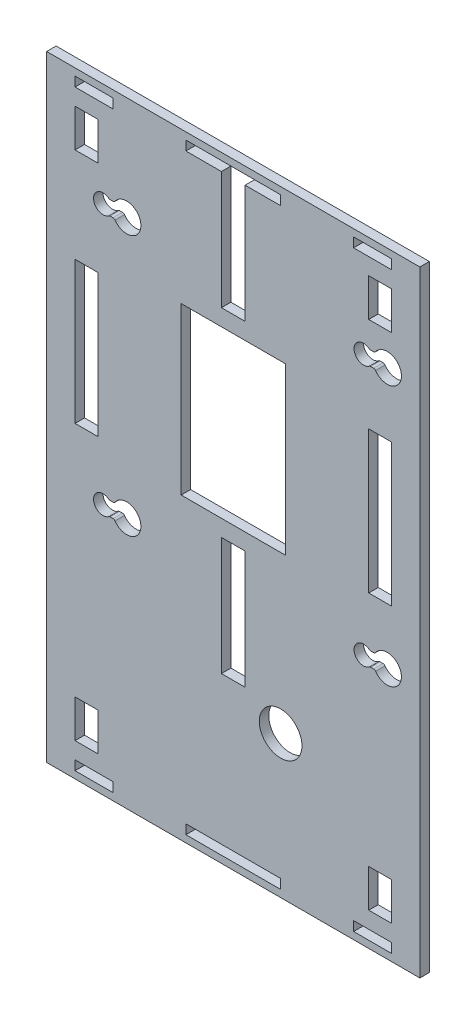
SolidWorks part; units mm, degrees
ref_plane "Front Plane" through (0, 0, 0) normal (0, 0, 1) x (1, 0, 0)
ref_plane "Top Plane" through (0, 0, 0) normal (0, 1, 0) x (1, 0, 0)
ref_plane "Right Plane" through (0, 0, 0) normal (1, 0, 0) x (0, 0, -1)
sketch "Sketch1" plane through (0, 0, 16.6) normal (0, 0, 1) x (1, 0, 0)
  line L0 (39.3947, 122.1963) -> (39.3947, 177.8037) construction
  line L1 (-39.3947, 70.4746) -> (39.3947, 70.4746)
  line L2 (-39.3947, 70.4746) -> (-39.3947, 200.4746)
  line L3 (-39.3947, 200.4746) -> (39.3947, 200.4746)
  line L4 (39.3947, 70.4746) -> (39.3947, 200.4746)
  line L5 (-39.3947, 70.4746) -> (39.3947, 200.4746) construction
  line L6 (-39.3947, 200.4746) -> (39.3947, 70.4746) construction
  line L8 (-39.3947, 177.8037) -> (-39.3947, 122.1963) construction
  line L10 (39.4486, 190.4746) -> (-39.4486, 190.4746) construction
  line L11 (39.4486, 190.4746) -> (-39.4486, 190.4746) construction
  point P0 (0, 135.4746)
  dimension "D1" = 130
  dimension "D2" = 10
extrude "panel" add sketch "Sketch1" along normal blind 2
sketch "Sketch2" plane through (0, 0, 18.6) normal (0, 0, 1) x (1, 0, 0)
  line L0 (-27.5, 151.08) -> (-39.3947, 151.08) construction
  line L1 (27.5, 123.58) -> (27.5, 178.58) construction
  line L2 (27.5, 123.58) -> (-27.5, 123.58) construction
  line L3 (-27.5, 123.58) -> (-27.5, 178.58) construction
  line L4 (27.5, 178.58) -> (-27.5, 178.58) construction
  line L5 (27.5, 123.58) -> (-27.5, 178.58) construction
  line L6 (-27.5, 123.58) -> (27.5, 178.58) construction
  line L7 (-39.3947, 200.4746) -> (-39.3947, 70.4746) construction
  line L8 (27.5, 151.08) -> (39.3947, 151.08) construction
  line L9 (39.3947, 70.4746) -> (39.3947, 200.4746) construction
  line L10 (-26.1771, 122.08) -> (-25.0981, 122.08)
  line L11 (-25.0981, 125.08) -> (-26.1771, 125.08)
  line L12 (-26.1771, 177.08) -> (-25.0981, 177.08)
  line L13 (-25.0981, 180.08) -> (-26.1771, 180.08)
  line L14 (28.8229, 177.08) -> (29.9019, 177.08)
  line L15 (29.9019, 180.08) -> (28.8229, 180.08)
  line L16 (28.8229, 122.08) -> (29.9019, 122.08)
  line L17 (29.9019, 125.08) -> (28.8229, 125.08)
  line L18 (0, 178.58) -> (0, 190.4746) construction
  line L20 (0, 190.4746) -> (0, 200.4746) construction
  line L21 (39.3947, 200.4746) -> (-39.3947, 200.4746) construction
  arc A0 (-26.0858, 124.9942) -> (-26.1771, 122.08) centre (-27.5, 123.58) ccw
  arc A1 (-25.0981, 122.08) -> (-25.0981, 125.08) centre (-22.5, 123.58) ccw
  arc A2 (-26.1771, 180.08) -> (-26.1771, 177.08) centre (-27.5, 178.58) ccw
  arc A3 (-25.0981, 177.08) -> (-25.0981, 180.08) centre (-22.5, 178.58) ccw
  arc A4 (28.8229, 180.08) -> (28.8229, 177.08) centre (27.5, 178.58) ccw
  arc A5 (29.9019, 177.08) -> (29.9019, 180.08) centre (32.5, 178.58) ccw
  arc A6 (28.8229, 125.08) -> (28.8229, 122.08) centre (27.5, 123.58) ccw
  arc A7 (29.9019, 122.08) -> (29.9019, 125.08) centre (32.5, 123.58) ccw
  point P0 (0, 151.08)
  dimension "D2" = 4
  dimension "D3" = 6
  dimension "D6" = 4
  dimension "D7" = 6
  dimension "D10" = 4
  dimension "D11" = 6
  dimension "D14" = 4
  dimension "D15" = 6
  dimension "D1" = 55
  dimension "D4" = 5
  dimension "D5" = 3
  dimension "D8" = 10
  dimension "D9" = 3
  dimension "D12" = 5
  dimension "D13" = 3
  dimension "D16" = 5
  dimension "D17" = 3
  dimension "D18" = 5
extrude "sucker holes" cut sketch "Sketch2" against normal up to next
fillet "Fillet1" radius 0.5 16 edges at (28.8229, 125.08, 17.6) (29.9019, 125.08, 17.6) (28.8229, 180.08, 17.6) (29.9019, 180.08, 17.6) (-25.0981, 180.08, 17.6) (-26.1771, 180.08, 17.6) (-26.1771, 177.08, 17.6) (-25.0981, 177.08, 17.6) (-26.1771, 122.08, 17.6) (-25.0981, 122.08, 17.6) (-26.1771, 125.08, 17.6) (-25.0981, 125.08, 17.6) (28.8229, 177.08, 17.6) (29.9019, 177.08, 17.6) (28.8229, 122.08, 17.6) (29.9019, 122.08, 17.6)
sketch "Sketch3" plane through (0, 0, 18.6) normal (0, 0, 1) x (1, 0, 0)
  line L0 (-27.5, 123.58) -> (27.5, 178.58) construction
  line L1 (-11, 133.58) -> (11, 133.58)
  line L2 (-11, 133.58) -> (-11, 168.58)
  line L3 (-11, 168.58) -> (11, 168.58)
  line L4 (11, 133.58) -> (11, 168.58)
  line L5 (-11, 133.58) -> (11, 168.58) construction
  line L6 (-11, 168.58) -> (11, 133.58) construction
  line L7 (0, 200.4746) -> (0, 70.4746) construction
  line L8 (39.3947, 200.4746) -> (-39.3947, 200.4746) construction
  line L9 (-39.3947, 70.4746) -> (39.3947, 70.4746) construction
  line L11 (-2.5, 196.9746) -> (2.5, 196.9746) construction
  line L12 (-2.5, 196.9746) -> (-2.5, 172.08)
  line L13 (-2.5, 172.08) -> (2.5, 172.08)
  line L14 (2.5, 196.9746) -> (2.5, 172.08)
  line L15 (-2.5, 196.9746) -> (2.5, 172.08) construction
  line L16 (-2.5, 172.08) -> (2.5, 196.9746) construction
  line L17 (-2.5, 130.08) -> (-2.5, 133.58) construction
  line L18 (-2.5, 130.08) -> (2.5, 130.08)
  line L19 (-2.5, 130.08) -> (-2.5, 105.1853)
  line L20 (-2.5, 105.1853) -> (2.5, 105.1853)
  line L21 (2.5, 130.08) -> (2.5, 105.1853)
  line L22 (-2.5, 130.08) -> (2.5, 105.1853) construction
  line L23 (-2.5, 105.1853) -> (2.5, 130.08) construction
  line L24 (-2.5, 172.08) -> (-2.5, 168.58) construction
  line L25 (-25.4, 73.9746) -> (-33.4, 73.9746)
  line L26 (-25.4, 73.9746) -> (-25.4, 71.9746)
  line L27 (-25.4, 71.9746) -> (-33.4, 71.9746)
  line L28 (-33.4, 73.9746) -> (-33.4, 71.9746)
  line L30 (-10, 198.9746) -> (10, 198.9746)
  line L31 (-10, 198.9746) -> (-10, 196.9746)
  line L32 (-10, 196.9746) -> (-2.5, 196.9746)
  line L33 (10, 198.9746) -> (10, 196.9746)
  line L34 (-10, 198.9746) -> (10, 196.9746) construction
  line L35 (-10, 196.9746) -> (10, 198.9746) construction
  line L36 (-25.4, 198.9746) -> (-33.4, 198.9746)
  line L37 (-25.4, 198.9746) -> (-25.4, 196.9746)
  line L38 (-25.4, 196.9746) -> (-33.4, 196.9746)
  line L39 (-33.4, 198.9746) -> (-33.4, 196.9746)
  line L40 (-25.4, 198.9746) -> (-33.4, 196.9746) construction
  line L41 (-25.4, 196.9746) -> (-33.4, 198.9746) construction
  line L42 (2.5, 196.9746) -> (10, 196.9746)
  line L43 (25.4, 198.9746) -> (33.4, 198.9746)
  line L44 (25.4, 198.9746) -> (25.4, 196.9746)
  line L45 (25.4, 196.9746) -> (33.4, 196.9746)
  line L46 (33.4, 198.9746) -> (33.4, 196.9746)
  line L47 (25.4, 198.9746) -> (33.4, 196.9746) construction
  line L48 (25.4, 196.9746) -> (33.4, 198.9746) construction
  line L49 (31, 200.4746) -> (31, 70.4746) construction
  line L50 (-28.6, 193.4746) -> (-33.4, 193.4746)
  line L51 (-28.6, 193.4746) -> (-28.6, 185.4746)
  line L52 (-28.6, 185.4746) -> (-33.4, 185.4746)
  line L53 (-33.4, 193.4746) -> (-33.4, 185.4746)
  line L54 (-28.6, 193.4746) -> (-33.4, 185.4746) construction
  line L55 (-28.6, 185.4746) -> (-33.4, 193.4746) construction
  line L56 (-28.6, 165.4746) -> (-33.4, 165.4746)
  line L57 (-28.6, 165.4746) -> (-28.6, 135.4746)
  line L58 (-28.6, 135.4746) -> (-33.4, 135.4746)
  line L59 (-33.4, 165.4746) -> (-33.4, 135.4746)
  line L60 (-28.6, 165.4746) -> (-33.4, 135.4746) construction
  line L61 (-28.6, 135.4746) -> (-33.4, 165.4746) construction
  line L62 (-28.6, 85.4746) -> (-33.4, 85.4746)
  line L63 (-28.6, 85.4746) -> (-28.6, 77.4746)
  line L64 (-28.6, 77.4746) -> (-33.4, 77.4746)
  line L65 (-33.4, 85.4746) -> (-33.4, 77.4746)
  line L66 (-28.6, 85.4746) -> (-33.4, 77.4746) construction
  line L67 (-28.6, 77.4746) -> (-33.4, 85.4746) construction
  line L68 (33.4, 85.4746) -> (28.6, 85.4746)
  line L69 (33.4, 85.4746) -> (33.4, 77.4746)
  line L70 (33.4, 77.4746) -> (28.6, 77.4746)
  line L71 (28.6, 85.4746) -> (28.6, 77.4746)
  line L72 (33.4, 85.4746) -> (28.6, 77.4746) construction
  line L73 (33.4, 77.4746) -> (28.6, 85.4746) construction
  line L74 (33.4, 165.4746) -> (28.6, 165.4746)
  line L75 (33.4, 165.4746) -> (33.4, 135.4746)
  line L76 (33.4, 135.4746) -> (28.6, 135.4746)
  line L77 (28.6, 165.4746) -> (28.6, 135.4746)
  line L78 (33.4, 165.4746) -> (28.6, 135.4746) construction
  line L79 (33.4, 135.4746) -> (28.6, 165.4746) construction
  line L80 (33.4, 193.4746) -> (28.6, 193.4746)
  line L81 (33.4, 193.4746) -> (33.4, 185.4746)
  line L82 (33.4, 185.4746) -> (28.6, 185.4746)
  line L83 (28.6, 193.4746) -> (28.6, 185.4746)
  line L84 (33.4, 193.4746) -> (28.6, 185.4746) construction
  line L85 (33.4, 185.4746) -> (28.6, 193.4746) construction
  line L86 (-25.4, 73.9746) -> (-33.4, 71.9746) construction
  line L87 (-31, 70.4746) -> (-31, 200.4746) construction
  line L88 (-25.4, 71.9746) -> (-33.4, 73.9746) construction
  line L89 (25.4, 73.9746) -> (33.4, 73.9746)
  line L90 (25.4, 73.9746) -> (25.4, 71.9746)
  line L91 (25.4, 71.9746) -> (33.4, 71.9746)
  line L92 (33.4, 73.9746) -> (33.4, 71.9746)
  line L93 (25.4, 73.9746) -> (33.4, 71.9746) construction
  line L94 (25.4, 71.9746) -> (33.4, 73.9746) construction
  line L95 (-10, 73.9746) -> (10, 73.9746)
  line L96 (-10, 73.9746) -> (-10, 71.9746)
  line L97 (-10, 71.9746) -> (10, 71.9746)
  line L98 (10, 73.9746) -> (10, 71.9746)
  line L99 (-10, 73.9746) -> (10, 71.9746) construction
  line L100 (-10, 71.9746) -> (10, 73.9746) construction
  point P0 (0, 151.08)
  point P15 (0, 184.5273)
  point P20 (0, 197.9746)
  point P22 (0, 117.6327)
  point P32 (-29.4, 197.9746)
  point P37 (-29.4, 72.9746)
  point P39 (29.4, 197.9746)
  point P44 (-31, 189.4746)
  point P49 (-31, 150.4746)
  point P54 (-31, 81.4746)
  point P59 (31, 81.4746)
  point P64 (31, 150.4746)
  point P69 (31, 189.4746)
  point P81 (29.4, 72.9746)
  point P86 (0, 72.9746)
  dimension "D1" = 3.5
  dimension "D2" = 3.5
  dimension "D3" = 35
  dimension "D4" = 22
  dimension "D5" = 5
  dimension "D6" = 2
  dimension "D7" = 20
  dimension "D8" = 8
  dimension "D9" = 62
  dimension "D10" = 7
  dimension "D11" = 8
  dimension "D12" = 30
  dimension "D13" = 4.8
  dimension "D14" = 35
  dimension "D15" = 7
  dimension "D16" = 1.5
extrude "side plate slots" cut sketch "Sketch3" against normal up to next
sketch "Sketch4" plane through (0, 0, 18.6) normal (0, 0, 1) x (1, 0, 0)
  arc A0 (4, 100.4746) -> (16, 100.4746) centre (10, 100.4746) ccw construction
  arc A1 (4, 100.4746) -> (16, 100.4746) centre (10, 100.4746) ccw construction
  circle A2 centre (10, 100.4746) radius 4.5
  dimension "D1" = 9
extrude "Cut-Extrude3" cut sketch "Sketch4" against normal up to next
